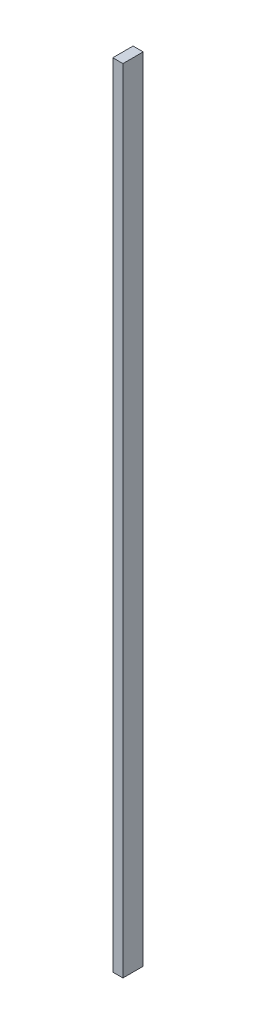
SolidWorks part; units mm, degrees
ref_plane "Спереди" through (0, 0, 0) normal (0, 0, 1) x (1, 0, 0)
ref_plane "Сверху" through (0, 0, 0) normal (0, 1, 0) x (1, 0, 0)
ref_plane "Справа" through (0, 0, 0) normal (1, 0, 0) x (0, 0, -1)
other "Configuration Table"
sketch "Эскиз1" plane through (0, 0, 0) normal (0, 1, 0) x (1, 0, 0)
  line L1 (12.5, 25) -> (-12.5, 25)
  line L2 (12.5, 25) -> (12.5, -25)
  line L3 (12.5, -25) -> (-12.5, -25)
  line L4 (-12.5, 25) -> (-12.5, -25)
  line L5 (12.5, 25) -> (-12.5, -25) construction
  line L6 (12.5, -25) -> (-12.5, 25) construction
  point P0 (0, 0)
extrude "Бобышка-Вытянуть1" add sketch "Эскиз1" along normal blind 1950
